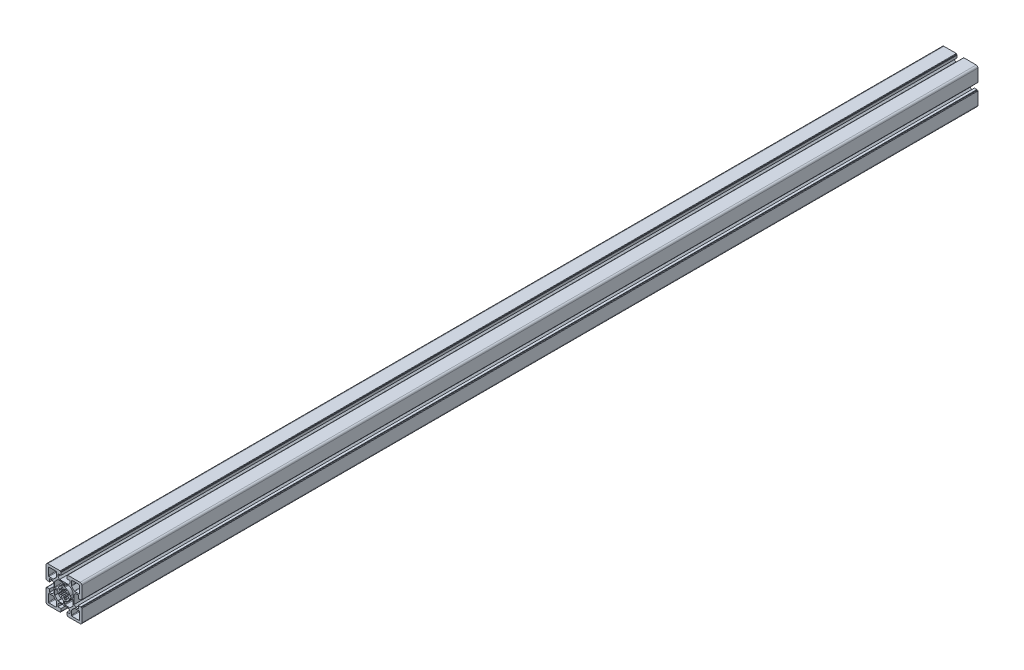
SolidWorks part; units mm, degrees
ref_plane "Front Plane" through (0, 0, 0) normal (0, 0, 1) x (1, 0, 0)
ref_plane "Top Plane" through (0, 0, 0) normal (0, 1, 0) x (1, 0, 0)
ref_plane "Right Plane" through (0, 0, 0) normal (1, 0, 0) x (0, 0, -1)
sketch "Sketch1" plane through (0, 0, 0) normal (0, 0, 1) x (1, 0, 0)
  line L0 (25, 12.3) -> (17.9642, 12.3)
  line L1 (17.2571, 12.5929) -> (12.5929, 17.2571)
  line L2 (12.3, 17.9642) -> (12.3, 25)
  line L3 (25, 26) -> (13.3, 26)
  line L4 (26, 13.3) -> (26, 25)
  line L5 (-0.8683, 4.924) -> (-1.3892, 7.8785)
  line L6 (-4.5886, 6.5532) -> (-2.8679, 4.0958)
  line L7 (-4.0958, 2.8679) -> (-6.5532, 4.5886)
  line L8 (-7.8785, 1.3892) -> (-4.9241, 0.8683)
  line L9 (14.5, 1) -> (10.9691, 1)
  line L10 (15.5, 2) -> (15.5, 9.9003)
  line L11 (15.3535, 10.2538) -> (10.2538, 15.3536)
  line L12 (9.9002, 15.5) -> (2, 15.5)
  line L13 (1, 10.9692) -> (1, 14.5)
  line L14 (7.25, 17) -> (0, 17)
  line L15 (10.05, 19.8) -> (7.25, 17)
  line L16 (10.05, 24) -> (10.05, 19.8)
  line L17 (5, 24) -> (10.05, 24)
  line L18 (5, 28.2) -> (5, 24)
  line L19 (5.5, 28.5) -> (5.3, 28.5)
  line L20 (5.8, 28.8) -> (5.8, 29.5)
  line L21 (27, 30) -> (6.3, 30)
  line L22 (30, 6.3) -> (30, 27)
  line L23 (29.5, 5.8) -> (28.8, 5.8)
  line L24 (28.5, 5.3) -> (28.5, 5.5)
  line L25 (24, 5) -> (28.2, 5)
  line L26 (24, 10.05) -> (24, 5)
  line L27 (19.8, 10.05) -> (24, 10.05)
  line L28 (17, 7.25) -> (19.8, 10.05)
  line L29 (17, 7.25) -> (17, 0)
  line L30 (7.8784, 1.3892) -> (4.924, 0.8683)
  line L31 (4.0957, 2.8679) -> (6.5532, 4.5886)
  line L32 (4.5886, 6.5532) -> (2.8679, 4.0958)
  line L33 (0.8682, 4.924) -> (1.3892, 7.8785)
  line L34 (-25, -12.3) -> (-17.9642, -12.3)
  line L35 (-17.2571, -12.5929) -> (-12.5929, -17.2571)
  line L36 (-12.3, -17.9642) -> (-12.3, -25)
  line L37 (-25, -26) -> (-13.3, -26)
  line L38 (-26, -13.3) -> (-26, -25)
  line L39 (-14.5, -1) -> (-10.9692, -1)
  line L40 (-15.5, -2) -> (-15.5, -9.9002)
  line L41 (-17, 7.25) -> (-17, 0)
  line L42 (-17, 7.25) -> (-19.8, 10.05)
  line L43 (-19.8, 10.05) -> (-24, 10.05)
  line L44 (-24, 10.05) -> (-24, 5)
  line L45 (-24, 5) -> (-28.2, 5)
  line L46 (-28.5, 5.3) -> (-28.5, 5.5)
  line L47 (-29.5, 5.8) -> (-28.8, 5.8)
  line L48 (-30, 6.3) -> (-30, 27)
  line L49 (-27, 30) -> (-6.3, 30)
  line L50 (-5.8, 28.8) -> (-5.8, 29.5)
  line L51 (-5.5, 28.5) -> (-5.3, 28.5)
  line L52 (-5, 28.2) -> (-5, 24)
  line L53 (-5, 24) -> (-10.05, 24)
  line L54 (-10.05, 24) -> (-10.05, 19.8)
  line L55 (-10.05, 19.8) -> (-7.25, 17)
  line L56 (-7.25, 17) -> (0, 17)
  line L57 (-15.3536, -10.2538) -> (-10.2538, -15.3535)
  line L58 (-9.9003, -15.5) -> (-2, -15.5)
  line L59 (-1, -10.9691) -> (-1, -14.5)
  line L60 (-7.25, -17) -> (0, -17)
  line L61 (-10.05, -19.8) -> (-7.25, -17)
  line L62 (-10.05, -24) -> (-10.05, -19.8)
  line L63 (-5, -24) -> (-10.05, -24)
  line L64 (-5, -28.2) -> (-5, -24)
  line L65 (-5.5, -28.5) -> (-5.3, -28.5)
  line L66 (-5.8, -28.8) -> (-5.8, -29.5)
  line L67 (-27, -30) -> (-6.3, -30)
  line L68 (-30, -6.3) -> (-30, -27)
  line L69 (-29.5, -5.8) -> (-28.8, -5.8)
  line L70 (-28.5, -5.3) -> (-28.5, -5.5)
  line L71 (-24, -5) -> (-28.2, -5)
  line L72 (-24, -10.05) -> (-24, -5)
  line L73 (-19.8, -10.05) -> (-24, -10.05)
  line L74 (-17, -7.25) -> (-19.8, -10.05)
  line L75 (-17, 0) -> (-17, -7.25)
  line L76 (0.8682, -4.924) -> (1.3892, -7.8784)
  line L77 (4.5886, -6.5532) -> (2.8679, -4.0957)
  line L78 (4.0957, -2.8679) -> (6.5532, -4.5886)
  line L79 (7.8784, -1.3892) -> (4.924, -0.8682)
  line L80 (17, 0) -> (17, -7.25)
  line L81 (17, -7.25) -> (19.8, -10.05)
  line L82 (19.8, -10.05) -> (24, -10.05)
  line L83 (24, -10.05) -> (24, -5)
  line L84 (24, -5) -> (28.2, -5)
  line L85 (28.5, -5.3) -> (28.5, -5.5)
  line L86 (29.5, -5.8) -> (28.8, -5.8)
  line L87 (30, -6.3) -> (30, -27)
  line L88 (27, -30) -> (6.3, -30)
  line L89 (5.8, -28.8) -> (5.8, -29.5)
  line L90 (5.5, -28.5) -> (5.3, -28.5)
  line L91 (5, -28.2) -> (5, -24)
  line L92 (5, -24) -> (10.05, -24)
  line L93 (10.05, -24) -> (10.05, -19.8)
  line L94 (10.05, -19.8) -> (7.25, -17)
  line L95 (7.25, -17) -> (0, -17)
  line L96 (1, -10.9691) -> (1, -14.5)
  line L97 (9.9002, -15.5) -> (2, -15.5)
  line L98 (15.3535, -10.2538) -> (10.2538, -15.3535)
  line L99 (15.5, -2) -> (15.5, -9.9002)
  line L100 (-1, 10.9692) -> (-1, 14.5)
  line L101 (-9.9003, 15.5) -> (-2, 15.5)
  line L102 (-15.3536, 10.2538) -> (-10.2538, 15.3536)
  line L103 (-15.5, 2) -> (-15.5, 9.9003)
  line L104 (-14.5, 1) -> (-10.9692, 1)
  line L105 (-26, 13.3) -> (-26, 25)
  line L106 (-25, 26) -> (-13.3, 26)
  line L107 (-12.3, 17.9642) -> (-12.3, 25)
  line L108 (-17.2571, 12.5929) -> (-12.5929, 17.2571)
  line L109 (-25, 12.3) -> (-17.9642, 12.3)
  line L110 (14.5, -1) -> (10.9691, -1)
  line L111 (-7.8785, -1.3892) -> (-4.9241, -0.8682)
  line L112 (-4.0958, -2.8679) -> (-6.5532, -4.5886)
  line L113 (-4.5886, -6.5532) -> (-2.8679, -4.0957)
  line L114 (-0.8683, -4.924) -> (-1.3892, -7.8784)
  line L115 (26, -13.3) -> (26, -25)
  line L116 (25, -26) -> (13.3, -26)
  line L117 (12.3, -17.9642) -> (12.3, -25)
  line L118 (17.2571, -12.5929) -> (12.5929, -17.2571)
  line L119 (25, -12.3) -> (17.9642, -12.3)
  line L120 (0, 0) -> (0, 50.387) construction
  line L121 (0, 0) -> (0, -41.9308) construction
  line L122 (0, 0) -> (51.9943, 0) construction
  line L123 (0, 0) -> (-54.8745, 0) construction
  arc A0 (17.9642, 12.3) -> (17.2571, 12.5929) centre (17.9642, 13.3) cw
  arc A1 (12.5929, 17.2571) -> (12.3, 17.9642) centre (13.3, 17.9642) cw
  arc A2 (12.3, 25) -> (13.3, 26) centre (13.3, 25) cw
  arc A3 (25, 26) -> (26, 25) centre (25, 25) cw
  arc A4 (26, 13.3) -> (25, 12.3) centre (25, 13.3) cw
  arc A5 (0, 5) -> (-0.8683, 4.924) centre (0, 0) ccw
  arc A6 (-1.3892, 7.8785) -> (-4.5886, 6.5532) centre (0, 0) ccw
  arc A7 (-2.8679, 4.0958) -> (-4.0958, 2.8679) centre (0, 0) ccw
  arc A8 (-6.5532, 4.5886) -> (-7.8785, 1.3892) centre (0, 0) ccw
  arc A9 (-4.9241, 0.8683) -> (-4.9241, -0.8682) centre (0, 0) ccw
  arc A10 (15.5, 2) -> (14.5, 1) centre (14.5, 2) cw
  arc A11 (15.3535, 10.2538) -> (15.5, 9.9003) centre (15, 9.9003) cw
  arc A12 (9.9002, 15.5) -> (10.2538, 15.3536) centre (9.9002, 15) cw
  arc A13 (1, 14.5) -> (2, 15.5) centre (2, 14.5) cw
  arc A14 (1.8206, 9.9854) -> (1, 10.9692) centre (2, 10.9692) cw
  arc A15 (1.8206, 9.9854) -> (9.9853, 1.8206) centre (0, 0) cw
  arc A16 (10.9691, 1) -> (9.9853, 1.8206) centre (10.9691, 2) cw
  arc A17 (5, 28.2) -> (5.3, 28.5) centre (5.3, 28.2) cw
  arc A18 (5.8, 28.8) -> (5.5, 28.5) centre (5.5, 28.8) cw
  arc A19 (5.8, 29.5) -> (6.3, 30) centre (6.3, 29.5) cw
  arc A20 (27, 30) -> (30, 27) centre (27, 27) cw
  arc A21 (30, 6.3) -> (29.5, 5.8) centre (29.5, 6.3) cw
  arc A22 (28.5, 5.5) -> (28.8, 5.8) centre (28.8, 5.5) cw
  arc A23 (28.5, 5.3) -> (28.2, 5) centre (28.2, 5.3) cw
  arc A24 (4.924, 0.8683) -> (4.924, -0.8682) centre (0, 0) cw
  arc A25 (6.5532, 4.5886) -> (7.8784, 1.3892) centre (0, 0) cw
  arc A26 (2.8679, 4.0958) -> (4.0957, 2.8679) centre (0, 0) cw
  arc A27 (1.3892, 7.8785) -> (4.5886, 6.5532) centre (0, 0) cw
  arc A28 (-28.5, 5.3) -> (-28.2, 5) centre (-28.2, 5.3) ccw
  arc A29 (-28.5, 5.5) -> (-28.8, 5.8) centre (-28.8, 5.5) ccw
  arc A30 (-30, 6.3) -> (-29.5, 5.8) centre (-29.5, 6.3) ccw
  arc A31 (-27, 30) -> (-30, 27) centre (-27, 27) ccw
  arc A32 (-5.8, 29.5) -> (-6.3, 30) centre (-6.3, 29.5) ccw
  arc A33 (-5.8, 28.8) -> (-5.5, 28.5) centre (-5.5, 28.8) ccw
  arc A34 (-5, 28.2) -> (-5.3, 28.5) centre (-5.3, 28.2) ccw
  arc A35 (0, 5) -> (0.8682, 4.924) centre (0, 0) cw
  arc A36 (-17.9642, -12.3) -> (-17.2571, -12.5929) centre (-17.9642, -13.3) cw
  arc A37 (-12.5929, -17.2571) -> (-12.3, -17.9642) centre (-13.3, -17.9642) cw
  arc A38 (-12.3, -25) -> (-13.3, -26) centre (-13.3, -25) cw
  arc A39 (-25, -26) -> (-26, -25) centre (-25, -25) cw
  arc A40 (-26, -13.3) -> (-25, -12.3) centre (-25, -13.3) cw
  arc A41 (-15.5, -2) -> (-14.5, -1) centre (-14.5, -2) cw
  arc A42 (-15.3536, -10.2538) -> (-15.5, -9.9002) centre (-15, -9.9002) cw
  arc A43 (-9.9003, -15.5) -> (-10.2538, -15.3535) centre (-9.9003, -15) cw
  arc A44 (-1, -14.5) -> (-2, -15.5) centre (-2, -14.5) cw
  arc A45 (-1.8206, -9.9853) -> (-1, -10.9691) centre (-2, -10.9691) cw
  arc A46 (-1.8206, -9.9853) -> (-9.9854, -1.8206) centre (0, 0) cw
  arc A47 (-10.9692, -1) -> (-9.9854, -1.8206) centre (-10.9692, -2) cw
  arc A48 (0, -4.9999) -> (0.8682, -4.924) centre (0, 0) ccw
  arc A49 (-5, -28.2) -> (-5.3, -28.5) centre (-5.3, -28.2) cw
  arc A50 (-5.8, -28.8) -> (-5.5, -28.5) centre (-5.5, -28.8) cw
  arc A51 (-5.8, -29.5) -> (-6.3, -30) centre (-6.3, -29.5) cw
  arc A52 (-27, -30) -> (-30, -27) centre (-27, -27) cw
  arc A53 (-30, -6.3) -> (-29.5, -5.8) centre (-29.5, -6.3) cw
  arc A54 (-28.5, -5.5) -> (-28.8, -5.8) centre (-28.8, -5.5) cw
  arc A55 (-28.5, -5.3) -> (-28.2, -5) centre (-28.2, -5.3) cw
  arc A56 (1.3892, -7.8784) -> (4.5886, -6.5532) centre (0, 0) ccw
  arc A57 (2.8679, -4.0957) -> (4.0957, -2.8679) centre (0, 0) ccw
  arc A58 (6.5532, -4.5886) -> (7.8784, -1.3892) centre (0, 0) ccw
  arc A59 (28.5, -5.3) -> (28.2, -5) centre (28.2, -5.3) ccw
  arc A60 (28.5, -5.5) -> (28.8, -5.8) centre (28.8, -5.5) ccw
  arc A61 (30, -6.3) -> (29.5, -5.8) centre (29.5, -6.3) ccw
  arc A62 (27, -30) -> (30, -27) centre (27, -27) ccw
  arc A63 (5.8, -29.5) -> (6.3, -30) centre (6.3, -29.5) ccw
  arc A64 (5.8, -28.8) -> (5.5, -28.5) centre (5.5, -28.8) ccw
  arc A65 (5, -28.2) -> (5.3, -28.5) centre (5.3, -28.2) ccw
  arc A66 (10.9691, -1) -> (9.9853, -1.8206) centre (10.9691, -2) ccw
  arc A67 (1.8206, -9.9853) -> (9.9853, -1.8206) centre (0, 0) ccw
  arc A68 (-10.9692, 1) -> (-9.9854, 1.8206) centre (-10.9692, 2) ccw
  arc A69 (-1.8206, 9.9854) -> (-9.9854, 1.8206) centre (0, 0) ccw
  arc A70 (-1.8206, 9.9854) -> (-1, 10.9692) centre (-2, 10.9692) ccw
  arc A71 (-1, 14.5) -> (-2, 15.5) centre (-2, 14.5) ccw
  arc A72 (-9.9003, 15.5) -> (-10.2538, 15.3536) centre (-9.9003, 15) ccw
  arc A73 (-15.3536, 10.2538) -> (-15.5, 9.9003) centre (-15, 9.9003) ccw
  arc A74 (-15.5, 2) -> (-14.5, 1) centre (-14.5, 2) ccw
  arc A75 (-26, 13.3) -> (-25, 12.3) centre (-25, 13.3) ccw
  arc A76 (-25, 26) -> (-26, 25) centre (-25, 25) ccw
  arc A77 (-12.3, 25) -> (-13.3, 26) centre (-13.3, 25) ccw
  arc A78 (-12.5929, 17.2571) -> (-12.3, 17.9642) centre (-13.3, 17.9642) ccw
  arc A79 (-17.9642, 12.3) -> (-17.2571, 12.5929) centre (-17.9642, 13.3) ccw
  arc A80 (1.8206, -9.9853) -> (1, -10.9691) centre (2, -10.9691) ccw
  arc A81 (1, -14.5) -> (2, -15.5) centre (2, -14.5) ccw
  arc A82 (9.9002, -15.5) -> (10.2538, -15.3535) centre (9.9002, -15) ccw
  arc A83 (15.3535, -10.2538) -> (15.5, -9.9002) centre (15, -9.9002) ccw
  arc A84 (15.5, -2) -> (14.5, -1) centre (14.5, -2) ccw
  arc A85 (-6.5532, -4.5886) -> (-7.8785, -1.3892) centre (0, 0) cw
  arc A86 (-2.8679, -4.0957) -> (-4.0958, -2.8679) centre (0, 0) cw
  arc A87 (-1.3892, -7.8784) -> (-4.5886, -6.5532) centre (0, 0) cw
  arc A88 (0, -4.9999) -> (-0.8683, -4.924) centre (0, 0) cw
  arc A89 (26, -13.3) -> (25, -12.3) centre (25, -13.3) ccw
  arc A90 (25, -26) -> (26, -25) centre (25, -25) ccw
  arc A91 (12.3, -25) -> (13.3, -26) centre (13.3, -25) ccw
  arc A92 (12.5929, -17.2571) -> (12.3, -17.9642) centre (13.3, -17.9642) ccw
  arc A93 (17.9642, -12.3) -> (17.2571, -12.5929) centre (17.9642, -13.3) ccw
  dimension "D6" = 13
  dimension "D4" = 10
  dimension "D1" = 60
  dimension "D2" = 60
  dimension "D3" = 30
  dimension "D5" = 10
extrude "Base-Extrude" add sketch "Sketch1" against normal blind 1500
scale "Escala1" scale about origin uniform scaling yes scale factor 0.5
